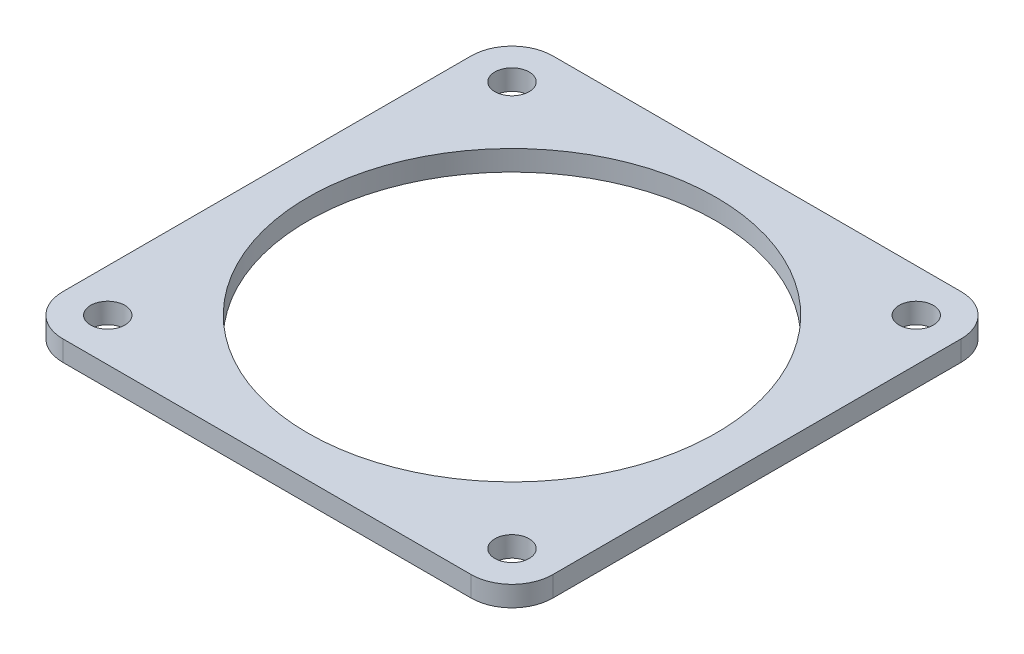
SolidWorks part; units mm, degrees
ref_plane "Front" through (0, 0, 0) normal (0, 0, 1) x (1, 0, 0)
ref_plane "Top" through (0, 0, 0) normal (0, 1, 0) x (1, 0, 0)
ref_plane "Right" through (0, 0, 0) normal (1, 0, 0) x (0, 0, -1)
sketch "Sketch1" plane through (0, 0, 0) normal (0, 1, 0) x (1, 0, 0)
  line L1 (-38.1, 38.1) -> (38.1, 38.1)
  line L2 (-38.1, 38.1) -> (-38.1, -38.1)
  line L3 (-38.1, -38.1) -> (38.1, -38.1)
  line L4 (38.1, 38.1) -> (38.1, -38.1)
  line L5 (-38.1, 38.1) -> (38.1, -38.1) construction
  line L6 (-38.1, -38.1) -> (38.1, 38.1) construction
  circle A0 centre (0, 0) radius 31.75
  point P0 (0, 0)
  dimension "D3" = 63.5
  dimension "D1" = 76.2
  dimension "D2" = 76.2
extrude "Boss-Extrude1" add sketch "Sketch1" along normal blind 3.175
sketch "Sketch2" plane through (0, 3.175, 0) normal (0, 1, 0) x (1, 0, 0)
  line L0 (38.1, 38.1) -> (0, 0) construction
  circle A0 centre (31.4309, 31.4309) radius 2.665
  circle A1 centre (0, 0) radius 31.75 construction
  dimension "D1" = 5.33
  dimension "D2" = 44.45
extrude "Cut-Extrude1" cut sketch "Sketch2" against normal up to next
pattern_circular "CirPattern1" count 4 over 360 about axis through (0, 0, 0) along (0, 1, 0) of "Cut-Extrude1"
fillet "Fillet1" radius 6.35 4 edges at (-38.1, 1.5875, -38.1) (38.1, 1.5875, -38.1) (38.1, 1.5875, 38.1) (-38.1, 1.5875, 38.1)
